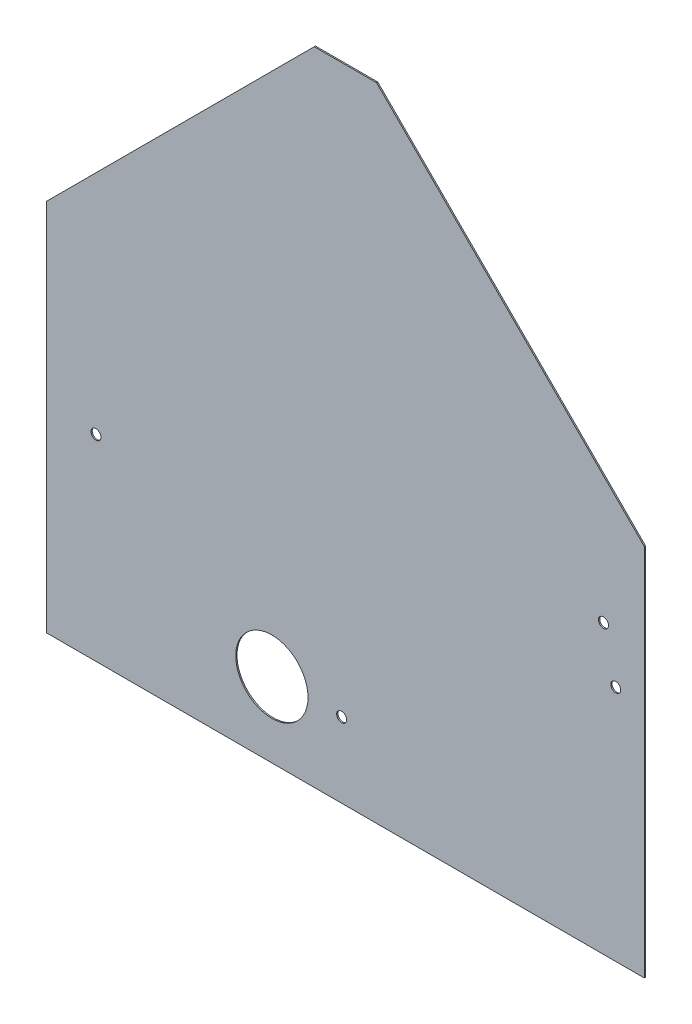
SolidWorks part; units mm, degrees
ref_plane "Plan de face" through (0, 0, 0) normal (0, 0, 1) x (1, 0, 0)
ref_plane "Plan de dessus" through (0, 0, 0) normal (0, 1, 0) x (1, 0, 0)
ref_plane "Plan de droite" through (0, 0, 0) normal (1, 0, 0) x (0, 0, -1)
sketch "Esquisse1" plane through (0, 0, 0) normal (0, 0, 1) x (1, 0, 0)
  line L0 (153.4897, 577.1727) -> (153.4897, -72.8273) construction
  line L1 (-217.641, 327.1727) -> (440.8093, 327.1727) construction
  line L2 (-86.5103, 327.1727) -> (-86.5103, 27.1727)
  line L4 (393.4897, 327.1727) -> (393.4897, 27.1727)
  line L6 (-86.5103, 327.1727) -> (128.4897, 542.1727)
  line L7 (393.4897, 327.1727) -> (178.4897, 542.1727)
  line L8 (128.4897, 542.1727) -> (178.4897, 542.1727)
  line L9 (94.4897, 87.1727) -> (153.4897, 87.1727) construction
  line L10 (-86.5103, -72.8273) -> (-86.5103, 27.1727) construction
  line L11 (-86.5103, 27.1727) -> (393.4897, 27.1727)
  line L12 (94.4897, 87.1727) -> (94.4897, 116.1727) construction
  circle A6 centre (150.4897, 87.1727) radius 4
  circle A7 centre (360.7215, 257.8508) radius 4
  circle A8 centre (-46.7603, 184.9727) radius 4
  circle A9 centre (370.5689, 217.8727) radius 4
  circle A10 centre (94.4897, 87.1727) radius 29
  dimension "D2" = 135
  dimension "D12" = 3
  dimension "D1" = 60
  dimension "D3" = 515
  dimension "D4" = 300
  dimension "D6" = 480
  dimension "D7" = 135
  dimension "D11" = 240
extrude "Boss.-Extru.1" add sketch "Esquisse1" along normal blind 1
